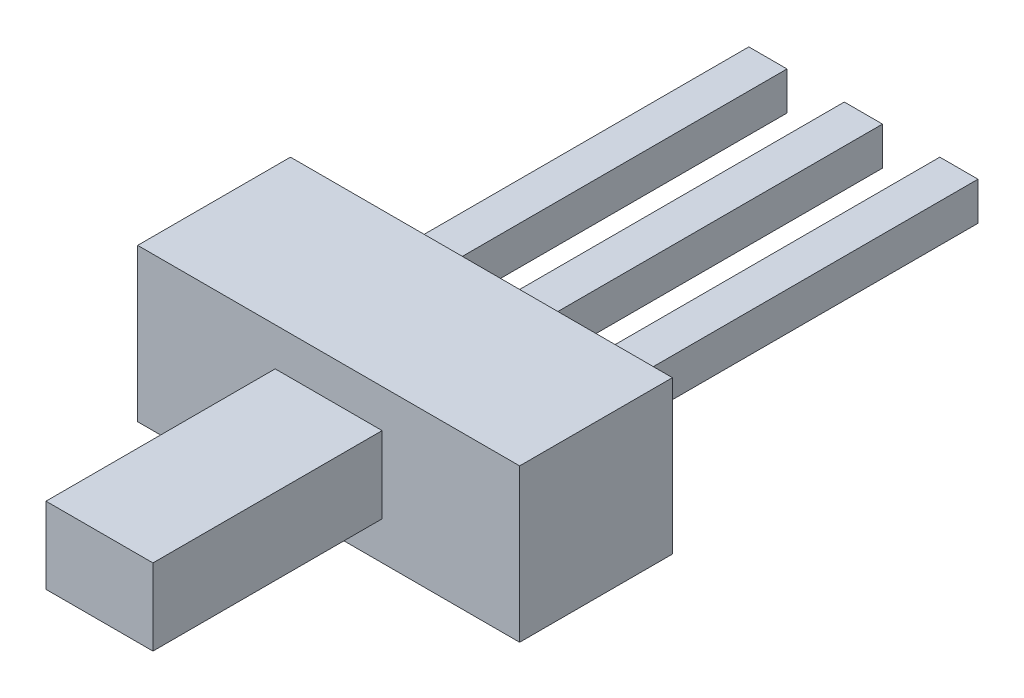
SolidWorks part; units mm, degrees
ref_plane "Спереди" through (0, 0, 0) normal (0, 0, 1) x (1, 0, 0)
ref_plane "Сверху" through (0, 0, 0) normal (0, 1, 0) x (1, 0, 0)
ref_plane "Справа" through (0, 0, 0) normal (1, 0, 0) x (0, 0, -1)
sketch "Эскиз1" plane through (0, 0, 0) normal (0, 0, 1) x (1, 0, 0)
  line L1 (0, 0) -> (5, 0)
  line L2 (0, 0) -> (0, -2)
  line L3 (0, -2) -> (5, -2)
  line L4 (5, 0) -> (5, -2)
  dimension "D1" = 2
  dimension "D2" = 5
extrude "Бобышка-Вытянуть1" add sketch "Эскиз1" along normal blind 2
sketch "Эскиз2" plane through (0, 0, 0) normal (0, 0, -1) x (-1, 0, 0)
  line L0 (0, -1) -> (-5, -1) construction
  line L1 (0, 0) -> (0, -2) construction
  line L2 (-5, -2) -> (-5, 0) construction
  line L3 (-1.25, -2) -> (-1.25, 0) construction
  line L4 (0, -2) -> (-5, -2) construction
  line L5 (-5, 0) -> (0, 0) construction
  line L6 (-3.75, -2) -> (-3.75, 0) construction
  line L7 (-2.5, -2) -> (-2.5, 0) construction
  line L9 (-1, -1.25) -> (-1.5, -1.25)
  line L10 (-1, -1.25) -> (-1, -0.75)
  line L11 (-1, -0.75) -> (-1.5, -0.75)
  line L12 (-1.5, -1.25) -> (-1.5, -0.75)
  line L13 (-1, -1.25) -> (-1.5, -0.75) construction
  line L14 (-1, -0.75) -> (-1.5, -1.25) construction
  line L15 (-2.25, -1.25) -> (-2.75, -1.25)
  line L16 (-2.25, -1.25) -> (-2.25, -0.75)
  line L17 (-2.25, -0.75) -> (-2.75, -0.75)
  line L18 (-2.75, -1.25) -> (-2.75, -0.75)
  line L19 (-2.25, -1.25) -> (-2.75, -0.75) construction
  line L20 (-2.25, -0.75) -> (-2.75, -1.25) construction
  line L21 (-3.5, -1.25) -> (-4, -1.25)
  line L22 (-3.5, -1.25) -> (-3.5, -0.75)
  line L23 (-3.5, -0.75) -> (-4, -0.75)
  line L24 (-4, -1.25) -> (-4, -0.75)
  line L25 (-3.5, -1.25) -> (-4, -0.75) construction
  line L26 (-3.5, -0.75) -> (-4, -1.25) construction
  point P16 (-1.25, -1)
  point P21 (-2.5, -1)
  point P26 (-3.75, -1)
  dimension "D1" = 1.25
  dimension "D2" = 1.25
  dimension "D3" = 0.5
  dimension "D4" = 0.5
  dimension "D5" = 0.5
  dimension "D6" = 0.5
  dimension "D7" = 0.5
  dimension "D8" = 0.5
extrude "Бобышка-Вытянуть2" add sketch "Эскиз2" along normal blind 5
sketch "Эскиз3" plane through (0, 0, 2) normal (0, 0, 1) x (1, 0, 0)
  line L0 (0, -1) -> (5, -1) construction
  line L1 (0, 0) -> (0, -2) construction
  line L2 (5, -2) -> (5, 0) construction
  line L3 (2.5, 0) -> (2.5, -2) construction
  line L4 (5, 0) -> (0, 0) construction
  line L5 (0, -2) -> (5, -2) construction
  line L7 (1.8, -0.5) -> (3.2, -0.5)
  line L8 (1.8, -0.5) -> (1.8, -1.5)
  line L9 (1.8, -1.5) -> (3.2, -1.5)
  line L10 (3.2, -0.5) -> (3.2, -1.5)
  line L11 (1.8, -0.5) -> (3.2, -1.5) construction
  line L12 (1.8, -1.5) -> (3.2, -0.5) construction
  point P12 (2.5, -1)
  dimension "D1" = 1.4
  dimension "D2" = 1
extrude "Бобышка-Вытянуть3" add sketch "Эскиз3" along normal blind 3
